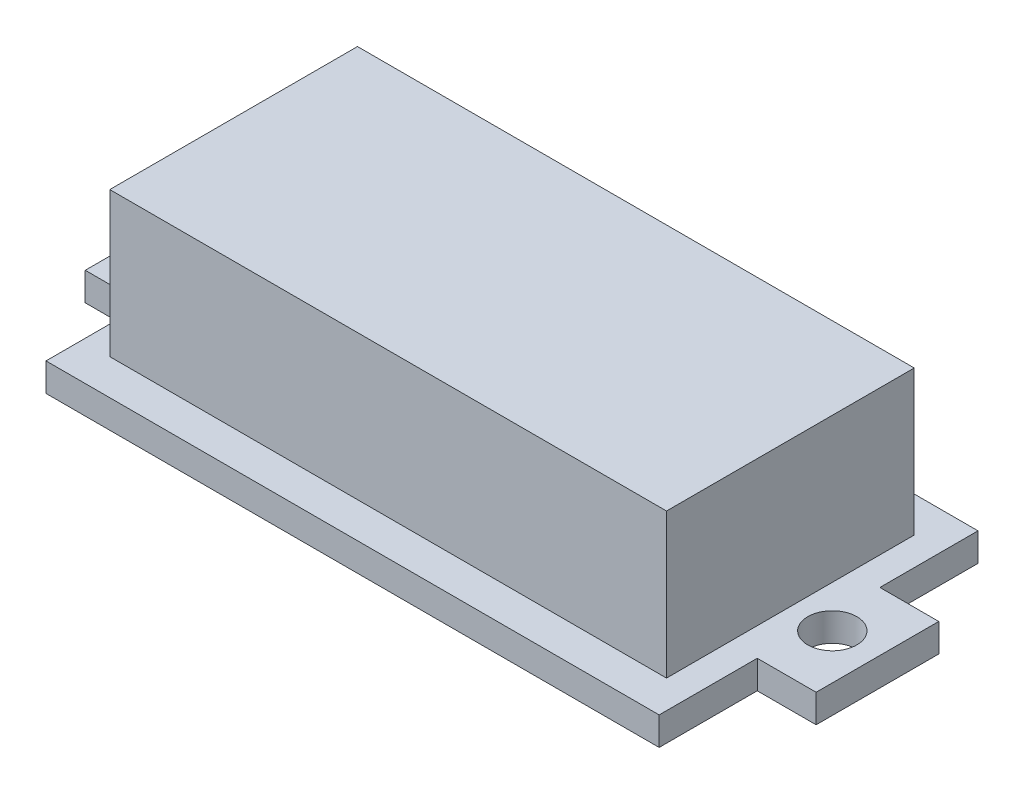
SolidWorks part; units mm, degrees
ref_plane "Front Plane" through (0, 0, 0) normal (0, 0, 1) x (1, 0, 0)
ref_plane "Top Plane" through (0, 0, 0) normal (0, 1, 0) x (1, 0, 0)
ref_plane "Right Plane" through (0, 0, 0) normal (1, 0, 0) x (0, 0, -1)
sketch "Sketch1" plane through (0, 0, 0) normal (0, 1, 0) x (1, 0, 0)
  line L0 (-12.5, 6.5) -> (12.5, 6.5)
  line L1 (12.5, 6.5) -> (12.5, 2.5)
  line L2 (12.5, 2.5) -> (14.9, 2.5)
  line L3 (14.9, 2.5) -> (14.9, -2.5)
  line L4 (14.9, -2.5) -> (12.5, -2.5)
  line L5 (12.5, -2.5) -> (12.5, -6.5)
  line L6 (12.5, -6.5) -> (-12.5, -6.5)
  line L7 (-12.5, -6.5) -> (-12.5, -2.5)
  line L8 (-12.5, -2.5) -> (-14.9, -2.5)
  line L9 (-14.9, -2.5) -> (-14.9, 2.5)
  line L10 (-14.9, 2.5) -> (-12.5, 2.5)
  line L11 (-12.5, 2.5) -> (-12.5, 6.5)
  line L12 (0, 0) -> (0, 6.5) construction
  line L13 (0, 0) -> (-14.9, 0) construction
  circle A0 centre (13.06, 0) radius 1
  circle A1 centre (-13.06, 0) radius 1
  point P3 (0, 6.5)
  point P21 (0, 0)
  dimension "D5" = 2
  dimension "D1" = 13
  dimension "D2" = 25
  dimension "D3" = 5
  dimension "D4" = 2.4
  dimension "D6" = 1.84
extrude "Boss-Extrude1" add sketch "Sketch1" along normal blind 1.15
sketch "Sketch2" plane through (0, 1.15, 0) normal (0, 1, 0) x (1, 0, 0)
  line L1 (-11.35, -5.05) -> (11.35, -5.05)
  line L2 (-11.35, -5.05) -> (-11.35, 5.05)
  line L3 (-11.35, 5.05) -> (11.35, 5.05)
  line L4 (11.35, -5.05) -> (11.35, 5.05)
  line L5 (-11.35, -5.05) -> (11.35, 5.05) construction
  line L6 (-11.35, 5.05) -> (11.35, -5.05) construction
  point P0 (0, 0)
  dimension "D1" = 10.1
  dimension "D2" = 22.7
extrude "Boss-Extrude2" add sketch "Sketch2" along normal blind 5.9
sketch "Sketch3" plane through (0, 0, -6.5) normal (0, 0, -1) x (-1, 0, 0)
  line L0 (-12.5, 0) -> (12.5, 0) construction
  line L1 (11.35, 7.05) -> (11.35, 1.15) construction
  circle A0 centre (8.85, 0) radius 0.68
  circle A1 centre (6.35, 0) radius 0.68
  point P6 (10.1691, 0)
  dimension "D1" = 1.36
  dimension "D2" = 2.5
  dimension "D3" = 2.5
extrude "Boss-Extrude3" add sketch "Sketch3" along normal blind 2 and the other way blind 0.5
